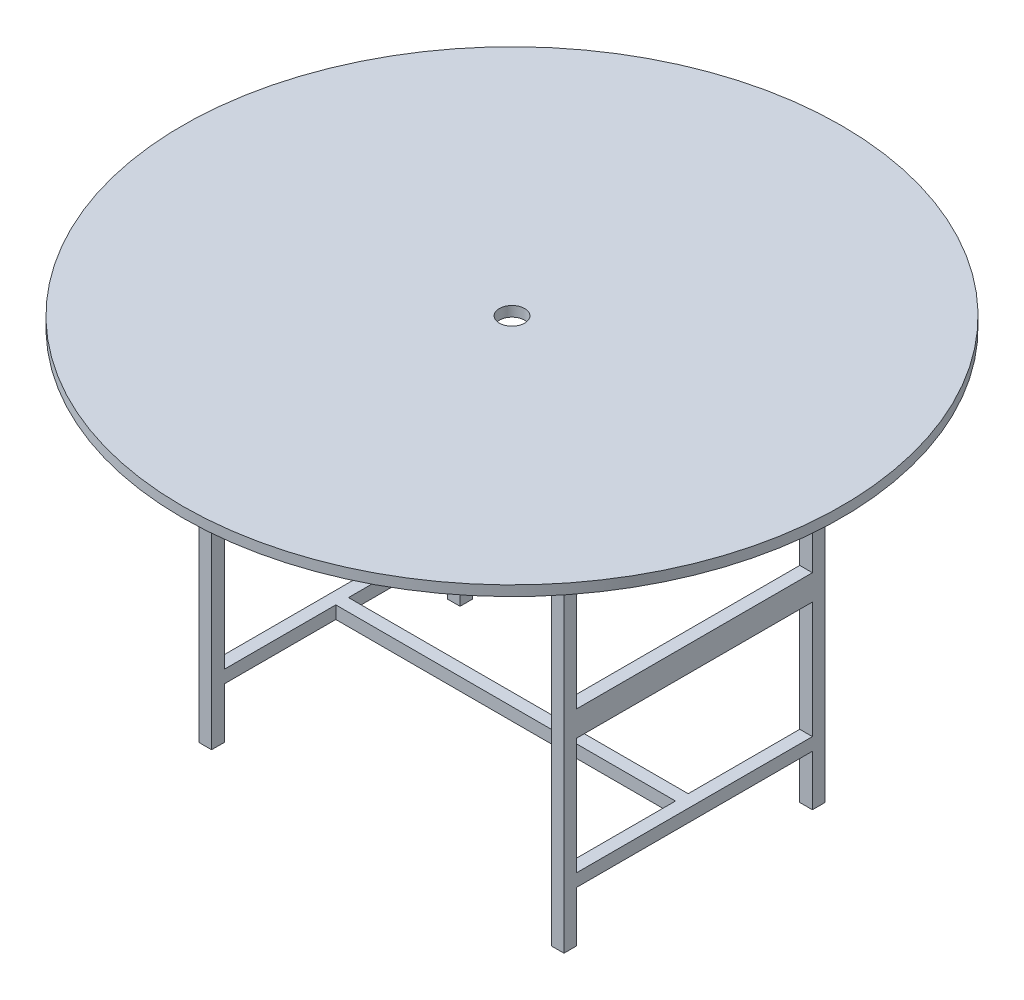
SolidWorks part; units mm, degrees
ref_plane "Front Plane" through (0, 0, 0) normal (0, 0, 1) x (1, 0, 0)
ref_plane "Top Plane" through (0, 0, 0) normal (0, 1, 0) x (1, 0, 0)
ref_plane "Right Plane" through (0, 0, 0) normal (1, 0, 0) x (0, 0, -1)
sketch "Sketch2" plane through (0, 0, 0) normal (0, 1, 0) x (1, 0, 0)
  line L1 (-78.7685, 441.1783) -> (-53.7685, 441.1783)
  line L2 (-78.7685, 441.1783) -> (-78.7685, 416.1783)
  line L3 (-78.7685, 416.1783) -> (-53.7685, 416.1783)
  line L4 (-53.7685, 441.1783) -> (-53.7685, 416.1783)
  line L5 (-78.7685, 441.1783) -> (-53.7685, 416.1783) construction
  line L6 (-78.7685, 416.1783) -> (-53.7685, 441.1783) construction
  line L11 (616.2315, 441.1783) -> (641.2315, 441.1783)
  line L12 (616.2315, 441.1783) -> (616.2315, 416.1783)
  line L13 (616.2315, 416.1783) -> (641.2315, 416.1783)
  line L14 (641.2315, 441.1783) -> (641.2315, 416.1783)
  line L15 (616.2315, 441.1783) -> (641.2315, 416.1783) construction
  line L16 (616.2315, 416.1783) -> (641.2315, 441.1783) construction
  line L17 (616.2315, -73.8217) -> (641.2315, -73.8217)
  line L18 (616.2315, -73.8217) -> (616.2315, -48.8217)
  line L19 (616.2315, -48.8217) -> (641.2315, -48.8217)
  line L20 (641.2315, -73.8217) -> (641.2315, -48.8217)
  line L21 (616.2315, -73.8217) -> (641.2315, -48.8217) construction
  line L22 (616.2315, -48.8217) -> (641.2315, -73.8217) construction
  line L23 (-78.7685, -48.8217) -> (-53.7685, -48.8217)
  line L24 (-78.7685, -48.8217) -> (-78.7685, -73.8217)
  line L25 (-78.7685, -73.8217) -> (-53.7685, -73.8217)
  line L26 (-53.7685, -48.8217) -> (-53.7685, -73.8217)
  line L27 (-78.7685, -48.8217) -> (-53.7685, -73.8217) construction
  line L28 (-78.7685, -73.8217) -> (-53.7685, -48.8217) construction
  point P0 (-66.2685, 428.6783)
  point P5 (-66.2685, 416.1783)
  point P6 (-66.2685, -48.8217)
  point P8 (628.7315, 416.1783)
  point P9 (628.7315, -48.8217)
  point P21 (-53.7685, 428.6783)
  point P22 (616.2315, 428.6783)
  point P23 (-53.7685, -61.3217)
  point P24 (616.2315, -61.3217)
  dimension "D1" = 25
  dimension "D2" = 25
  dimension "D3" = 25
  dimension "D4" = 25
  dimension "D5" = 25
  dimension "D6" = 25
  dimension "D7" = 25
  dimension "D8" = 25
  dimension "D9" = 465
  dimension "D10" = 465
  dimension "D11" = 670
  dimension "D12" = 670
extrude "Boss-Extrude1" add sketch "Sketch2" against normal blind 760
sketch "Sketch3" plane through (0, 0, -416.1783) normal (0, 0, 1) x (1, 0, 0)
  line L0 (-53.7685, -760) -> (-53.7685, -660)
  line L1 (-53.7685, -760) -> (-53.7685, 0) construction
  line L2 (641.2315, -760) -> (641.2315, -660)
  line L3 (641.2315, -760) -> (641.2315, 0) construction
  line L4 (616.2315, -760) -> (641.2315, -760) construction
  line L5 (-53.7685, -660) -> (-78.7685, -660)
  line L6 (-78.7685, -760) -> (-78.7685, 0) construction
  line L7 (-78.7685, -660) -> (-78.7685, -635)
  line L8 (-78.7685, -635) -> (-53.7685, -635)
  line L9 (-53.7685, -635) -> (-53.7685, -660)
  line L10 (641.2315, -660) -> (616.2315, -660)
  line L11 (616.2315, -760) -> (616.2315, 0) construction
  line L12 (616.2315, -660) -> (616.2315, -635)
  line L13 (616.2315, -635) -> (641.2315, -635)
  line L14 (641.2315, -635) -> (641.2315, -660)
  line M8 (-78.7685, 0) -> (-78.7685, -760)
  line M10 (-53.7685, -760) -> (-53.7685, 0)
  dimension "D1" = 100
  dimension "D2" = 100
  dimension "D3" = 25
  dimension "D4" = 25
  dimension "D5" = 25
  dimension "D6" = 25
extrude "Boss-Extrude2" add sketch "Sketch3" along normal blind 470 contours L8 L5 M8 M10 | L14 L13 L12 L10
sketch "Sketch6" plane through (-53.7685, 0, 0) normal (1, 0, 0) x (0, 0, -1)
  line L0 (-48.8217, -635) -> (183.6783, -635)
  line L1 (-48.8217, -635) -> (416.1783, -635) construction
  line L2 (-48.8217, -660) -> (416.1783, -660) construction
  line L4 (171.1783, -635) -> (171.1783, -660)
  line L5 (171.1783, -660) -> (196.1783, -660)
  line L6 (196.1783, -635) -> (196.1783, -660)
  line L7 (171.1783, -635) -> (196.1783, -660) construction
  line L8 (196.1783, -635) -> (171.1783, -660) construction
  line L9 (171.1783, -635) -> (196.1783, -635)
  line L10 (-48.8217, 0) -> (-48.8217, -100)
  line L11 (-48.8217, -635) -> (-48.8217, 0) construction
  line L12 (416.1783, 0) -> (416.1783, -100)
  line L13 (416.1783, -635) -> (416.1783, 0) construction
  line L14 (-48.8217, -100) -> (-73.8217, -100)
  line L15 (-73.8217, -760) -> (-73.8217, 0) construction
  line L16 (-73.8217, -100) -> (-73.8217, -125)
  line L17 (-73.8217, -125) -> (-48.8217, -125)
  line L18 (-48.8217, -125) -> (-48.8217, -100)
  line L19 (416.1783, -100) -> (441.1783, -100)
  line L20 (441.1783, -760) -> (441.1783, 0) construction
  line L21 (441.1783, -100) -> (441.1783, -125)
  line L22 (441.1783, -125) -> (416.1783, -125)
  line L23 (416.1783, -125) -> (416.1783, -100)
  line L24 (416.1783, -100) -> (416.1783, -125)
  point P6 (183.6783, -647.5)
  line M16 (441.1783, -760) -> (441.1783, 0)
  line M18 (416.1783, 0) -> (416.1783, -635)
  dimension "D1" = 25
  dimension "D2" = 100
  dimension "D3" = 100
  dimension "D4" = 25
  dimension "D5" = 25
extrude "Boss-Extrude4" add sketch "Sketch6" along normal blind 675 contours L22 L19 M16 M18 | L4 L5 L6 L9 | L14 L16 L17 L18
sketch "Sketch10" plane through (0, 0, 48.8217) normal (0, 0, -1) x (-1, 0, 0)
  line L0 (-616.2315, -125) -> (-641.2315, -125)
  line L1 (-641.2315, -760) -> (-641.2315, 0) construction
  line L2 (-641.2315, -125) -> (-641.2315, -100)
  line L3 (-641.2315, -100) -> (-616.2315, -100)
  line L4 (-616.2315, -100) -> (-616.2315, -125)
  line L5 (53.7685, -100) -> (78.7685, -100)
  line L6 (78.7685, -760) -> (78.7685, 0) construction
  line L7 (78.7685, -100) -> (78.7685, -125)
  line L8 (78.7685, -125) -> (53.7685, -125)
  line L9 (53.7685, -125) -> (53.7685, -100)
extrude "Boss-Extrude5" add sketch "Sketch10" along normal blind 470
sketch "Sketch11" plane through (0, 0, 48.8217) normal (0, 0, -1) x (-1, 0, 0)
  line L0 (-616.2315, -635.101) -> (-616.2315, -405.101)
  line L1 (-616.2315, -760) -> (-616.2315, -125) construction
  line L2 (-616.2315, -405.101) -> (-641.2315, -405.101)
  line L3 (-641.2315, -760) -> (-641.2315, 0) construction
  line L4 (-641.2315, -405.101) -> (-641.2315, -355.101)
  line L5 (-641.2315, -355.101) -> (-616.2315, -355.101)
  line L6 (-616.2315, -355.101) -> (-616.2315, -405.101)
  line M7 (-641.2315, -125) -> (-641.2315, -635)
  line M9 (-616.2315, -635) -> (-616.2315, -125)
  dimension "D1" = 230
  dimension "D2" = 50
extrude "Boss-Extrude6" add sketch "Sketch11" along normal blind 470 contours L5 L2 M7 M9
sketch "Sketch12" plane through (0, 0, 0) normal (0, 1, 0) x (1, 0, 0)
  line L0 (-53.7685, 416.1783) -> (616.2315, -48.8217) construction
  line L1 (-53.7685, -48.8217) -> (616.2315, 416.1783) construction
  circle A0 centre (281.2315, 183.6783) radius 650
  dimension "D1" = 1300
extrude "Boss-Extrude7" add sketch "Sketch12" along normal blind 20
sketch "Sketch13" plane through (0, 0, 0) normal (0, 1, 0) x (1, 0, 0)
  circle A0 centre (281.2315, 183.6783) radius 25
  dimension "D1" = 50
extrude "Cut-Extrude3" cut sketch "Sketch13" along normal blind 20 contours A0
sketch "Sketch15" plane through (0, 20, 0) normal (0, 1, 0) x (1, 0, 0)
  circle A0 centre (281.2315, 183.6783) radius 25
